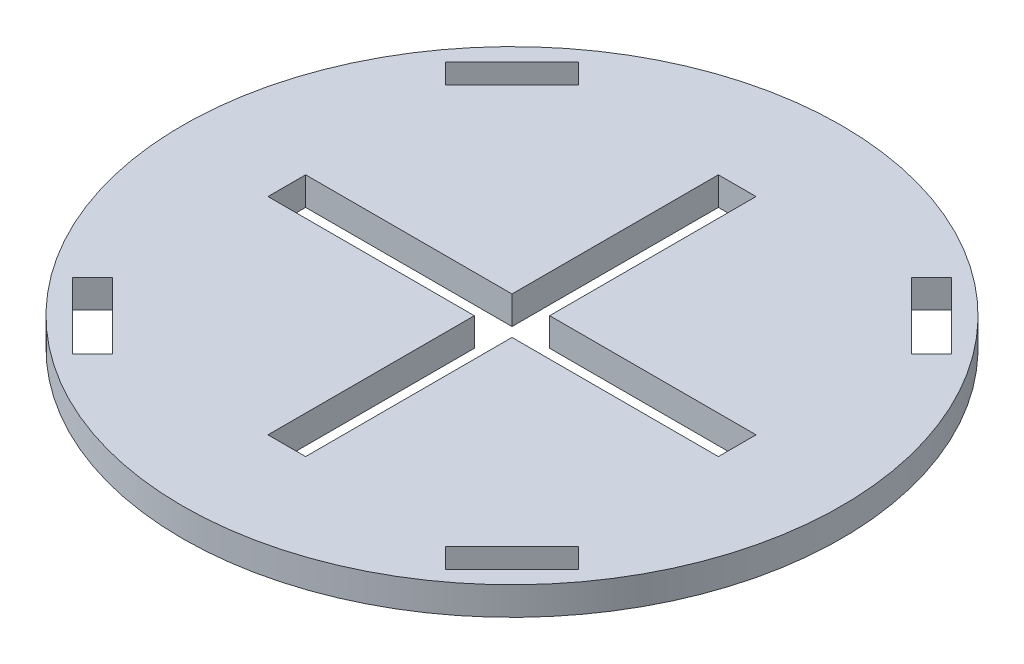
SolidWorks part; units mm, degrees
ref_plane "Přední rovina" through (0, 0, 0) normal (0, 0, 1) x (1, 0, 0)
ref_plane "Horní rovina" through (0, 0, 0) normal (0, 1, 0) x (1, 0, 0)
ref_plane "Pravá rovina" through (0, 0, 0) normal (1, 0, 0) x (0, 0, -1)
sketch "Skica1" plane through (0, 0, 0) normal (0, 1, 0) x (1, 0, 0)
  circle A0 centre (0, 0) radius 35
  dimension "D1" = 70
extrude "Přidat vysunutím1" add sketch "Skica1" along normal blind 3
sketch "Skica2" plane through (0, 3, 0) normal (0, 1, 0) x (1, 0, 0)
  line L0 (0, 69.5494) -> (0, -66.8377) construction
  line L1 (39.3171, 0) -> (-56.191, 0) construction
  line L2 (2, 23.9165) -> (2, 2)
  line L3 (-2, 23.9165) -> (2, 23.9165)
  line L5 (-2, -23.9165) -> (2, -23.9165)
  line L7 (-2, 23.9165) -> (2, -23.9165) construction
  line L8 (-2, -23.9165) -> (2, 23.9165) construction
  line L21 (2, 2) -> (23.9165, 2)
  line L23 (2, -2) -> (23.9165, -2)
  line L24 (23.9165, 2) -> (23.9165, -2)
  line L25 (2, 2) -> (23.9165, -2) construction
  line L26 (2, -2) -> (23.9165, 2) construction
  line L27 (2, -2) -> (2, -23.9165)
  line L28 (-2, -23.9165) -> (-2, -2)
  line L29 (-2, 23.9165) -> (-2, 2)
  line L30 (-2, 2) -> (-23.9165, 2)
  line L31 (-2, -2) -> (-23.9165, -2)
  line L32 (-23.9165, -2) -> (-23.9165, 2)
  circle A0 centre (0, 0) radius 24 construction
  point P11 (12.9583, 0)
  dimension "D1" = 48
  dimension "D3" = 4
  dimension "D4" = 4
extrude "Odebrat vysunutím1" cut sketch "Skica2" against normal blind 3
sketch "Skica3" plane through (0, 3, 0) normal (0, 1, 0) x (1, 0, 0)
  line L0 (43.0106, 0) -> (-46.9938, 0) construction
  line L1 (0, 62.7342) -> (0, -56.6891) construction
  line L2 (32.883, -32.883) -> (-52.0969, 52.0969) construction
  line L3 (32.883, 32.883) -> (-52.0969, -52.0969) construction
  line L4 (19.799, 26.8701) -> (26.8701, 19.799)
  line L5 (19.799, 26.8701) -> (17.6777, 24.7487)
  line L6 (26.8701, 19.799) -> (24.7487, 17.6777)
  line L7 (17.6777, 24.7487) -> (24.7487, 17.6777)
  line L8 (19.799, 26.8701) -> (24.7487, 17.6777) construction
  line L9 (26.8701, 19.799) -> (17.6777, 24.7487) construction
  line L10 (26.8701, -19.799) -> (19.799, -26.8701)
  line L11 (26.8701, -19.799) -> (24.7487, -17.6777)
  line L12 (24.7487, -17.6777) -> (17.6777, -24.7487)
  line L13 (19.799, -26.8701) -> (17.6777, -24.7487)
  line L14 (26.8701, -19.799) -> (17.6777, -24.7487) construction
  line L15 (19.799, -26.8701) -> (24.7487, -17.6777) construction
  line L16 (-19.799, -26.8701) -> (-26.8701, -19.799)
  line L17 (-19.799, -26.8701) -> (-17.6777, -24.7487)
  line L18 (-17.6777, -24.7487) -> (-24.7487, -17.6777)
  line L19 (-26.8701, -19.799) -> (-24.7487, -17.6777)
  line L20 (-19.799, -26.8701) -> (-24.7487, -17.6777) construction
  line L21 (-26.8701, -19.799) -> (-17.6777, -24.7487) construction
  line L22 (-26.8701, 19.799) -> (-19.799, 26.8701)
  line L23 (-26.8701, 19.799) -> (-24.7487, 17.6777)
  line L24 (-24.7487, 17.6777) -> (-17.6777, 24.7487)
  line L25 (-19.799, 26.8701) -> (-17.6777, 24.7487)
  line L26 (-26.8701, 19.799) -> (-17.6777, 24.7487) construction
  line L27 (-19.799, 26.8701) -> (-24.7487, 17.6777) construction
  circle A0 centre (0, 0) radius 35 construction
  point P10 (22.2739, 22.2739)
  point P19 (22.2739, -22.2739)
  point P24 (-22.2739, -22.2739)
  point P29 (-22.2739, 22.2739)
  point P34 (0, 0)
  dimension "D1" = 45
  dimension "D2" = 10
  dimension "D3" = 3
  dimension "D4" = 30
  dimension "D5" = 4
extrude "Odebrat vysunutím3" cut sketch "Skica3" against normal blind 3
